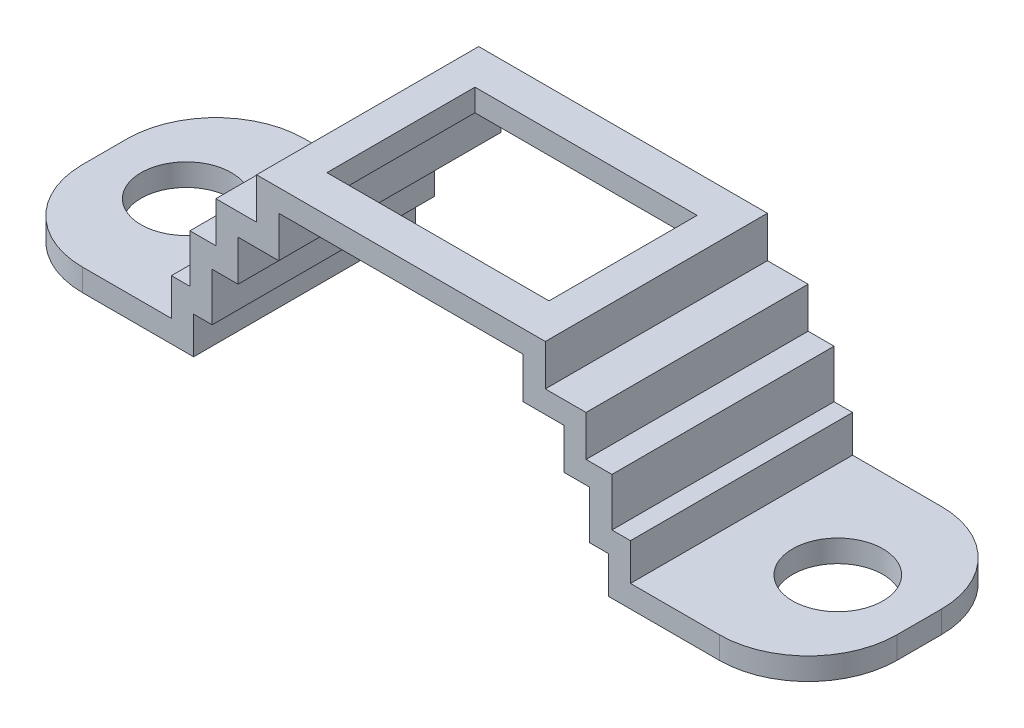
SolidWorks part; units mm, degrees
material "PBT General Purpose"
ref_plane "Front Plane" through (0, 0, 0) normal (0, 0, 1) x (1, 0, 0)
ref_plane "Top Plane" through (0, 0, 0) normal (0, 1, 0) x (1, 0, 0)
ref_plane "Right Plane" through (0, 0, 0) normal (1, 0, 0) x (0, 0, -1)
sketch "Sketch1" plane through (0, 0, 0) normal (0, 0, 1) x (1, 0, 0)
  line L0 (-55, 4.5) -> (-28, 4.5)
  line L1 (-28, 4.5) -> (-28, 9.5)
  line L2 (-28, 9.5) -> (-25.5, 9.5)
  line L3 (-25.5, 9.5) -> (-25.5, 16)
  line L4 (-25.5, 16) -> (-22, 16)
  line L5 (-22, 16) -> (-22, 21.5)
  line L6 (-22, 21.5) -> (-16.5, 21.5)
  line L7 (-16.5, 21.5) -> (-16.5, 27.05)
  line L8 (-16.5, 27.05) -> (0, 27.05)
  circle A0 centre (0, 0) radius 27.05
  dimension "D1" = 54.1
  dimension "D2" = 27
  dimension "D3" = 4.5
  dimension "D4" = 28
  dimension "D5" = 5
  dimension "D6" = 2.5
  dimension "D7" = 6.5
  dimension "D8" = 3.5
  dimension "D9" = 5.5
  dimension "D10" = 5.5
  dimension "D11" = 16.5
  dimension "D12" = 5.55
extrude "Extrude-Thin1" add sketch "Sketch1" along normal mid plane 30 thin contours L0 L1 L2 L3 L4 L5 L6 L7 L8
sketch "Sketch2" plane through (0, 7.5, 0) normal (0, 1, 0) x (1, 0, 0)
  line L0 (0, -15) -> (0, 15) construction
  circle A0 centre (-44, 0) radius 6.1
  dimension "D1" = 12.2
  dimension "D2" = 44
extrude "Cut-Extrude1" cut sketch "Sketch2" against normal through all
fillet "Fillet1" radius 12 2 edges at (-55, 6, -15) (-55, 6, 15)
mirror "Mirror1" about plane through (0, 30.05, 15) normal (1, 0, 0) of "Fillet1", "Cut-Extrude1", "Extrude-Thin1"
sketch "Sketch3" plane through (0, 30.05, 0) normal (0, 1, 0) x (1, 0, 0)
  line L1 (15, -10) -> (-15, -10)
  line L2 (15, -10) -> (15, 10)
  line L3 (15, 10) -> (-15, 10)
  line L4 (-15, -10) -> (-15, 10)
  line L5 (15, -10) -> (-15, 10) construction
  line L6 (15, 10) -> (-15, -10) construction
  point P0 (0, 0)
  dimension "D1" = 30
  dimension "D2" = 20
extrude "Cut-Extrude2" cut sketch "Sketch3" against normal through all
